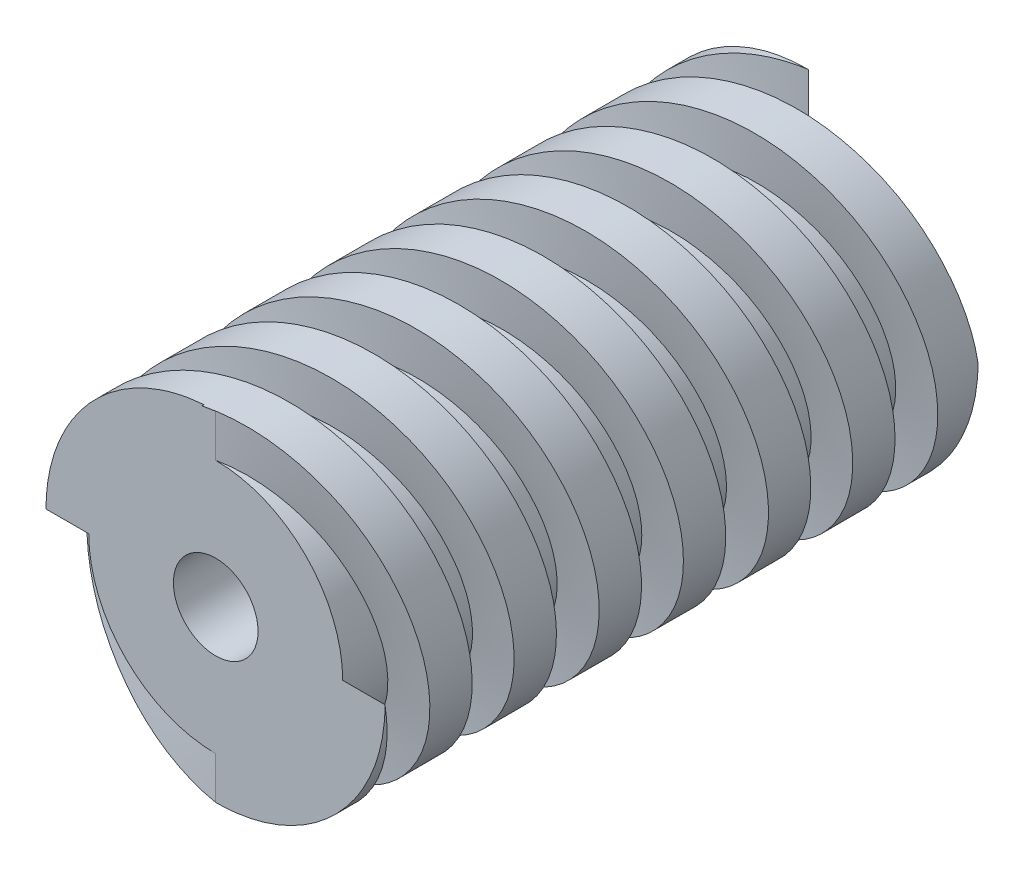
SolidWorks part; units mm, degrees
ref_plane "Front Plane" through (0, 0, 0) normal (0, 0, 1) x (1, 0, 0)
ref_plane "Top Plane" through (0, 0, 0) normal (0, 1, 0) x (1, 0, 0)
ref_plane "Right Plane" through (0, 0, 0) normal (1, 0, 0) x (0, 0, -1)
sketch "Sketch2" plane through (0, 0, 0) normal (0, 0, 1) x (1, 0, 0)
  circle A0 centre (0, 0) radius 1.5
extrude "Boss-Extrude1" add sketch "Sketch2" along normal blind 7
ref_plane "Plane1" through (0, 0, 7.5) normal (0, 0, 1) x (1, 0, 0)
sketch "Sketch3" plane through (0, 0, 7.5) normal (0, 0, 1) x (1, 0, 0)
  circle A0 centre (0, 0) radius 2
curve "Helix/Spiral1" pitch 2 height 7.5 turns 3.75
sketch "Sketch4" plane through (0, 0, 7.5) normal (0, 0, 1) x (1, 0, 0)
  circle A0 centre (0, 0) radius 2
curve "Helix/Spiral2" pitch 2 height 7.5 turns 3.75
sketch "Sketch5" plane through (0, 0, 0) normal (0, 1, 0) x (1, 0, 0)
  line L0 (-1.65, -7.5) -> (1.65, -7.5) construction
  line L1 (-1.5, -7.5) -> (-2.0049, -7.5)
  line L2 (-1.5, -7.5) -> (-1.5, -7)
  line L3 (-1.5, -7) -> (-2.0049, -7)
  line L4 (-2.0049, -7.5) -> (-2.0049, -7)
  dimension "D1" = 0.5049
  dimension "D2" = 0.5
sweep "Sweep1" add profiles "Sketch5" path "Helix/Spiral1"
sketch "Sketch6" plane through (0, 0, 0) normal (0, 1, 0) x (1, 0, 0)
  line L0 (-1.65, -7.5) -> (1.65, -7.5) construction
  line L1 (1.5, -7.5) -> (2, -7.5)
  line L2 (1.5, -7.5) -> (1.5, -7)
  line L3 (1.5, -7) -> (2, -7)
  line L4 (2, -7.5) -> (2, -7)
  dimension "D1" = 0.5
  dimension "D2" = 0.5
sweep "Sweep2" add profiles "Sketch6" path "Helix/Spiral2"
sketch "Sketch8" plane through (0, 0, 0) normal (1, 0, 0) x (0, 0, -1)
  line L0 (-7, 1.5) -> (-7, 0) construction
  line L1 (-7, 2) -> (-7.5, 2)
  line L2 (-7, 2) -> (-7, -2)
  line L3 (-7, -2) -> (-7.5, -2)
  line L4 (-7.5, 2) -> (-7.5, -2)
  line L5 (-7.5, 1.65) -> (-7.5, -1.65) construction
  line L6 (-7.5, 0) -> (-7, 0) construction
  line L7 (0.5, 2) -> (0, 2)
  line L8 (0.5, 2) -> (0.5, -2.2212)
  line L9 (0.5, -2.2212) -> (0, -2.2212)
  line L10 (0, 2) -> (0, -2.2212)
  line L11 (0, 2) -> (0, 1.5) construction
  line L12 (0.5, 2) -> (0, 2) construction
  point P8 (-7, 0)
  dimension "D1" = 4
  dimension "D2" = 0
  dimension "D3" = 0
  dimension "D4" = 0
extrude "Cut-Extrude1" cut sketch "Sketch8" against normal through all and the other way through all
sketch "Sketch9" plane through (0, 0, 7) normal (0, 0, 1) x (1, 0, 0)
  circle A0 centre (0, 0) radius 0.5
extrude "Cut-Extrude2" cut sketch "Sketch9" against normal through all
